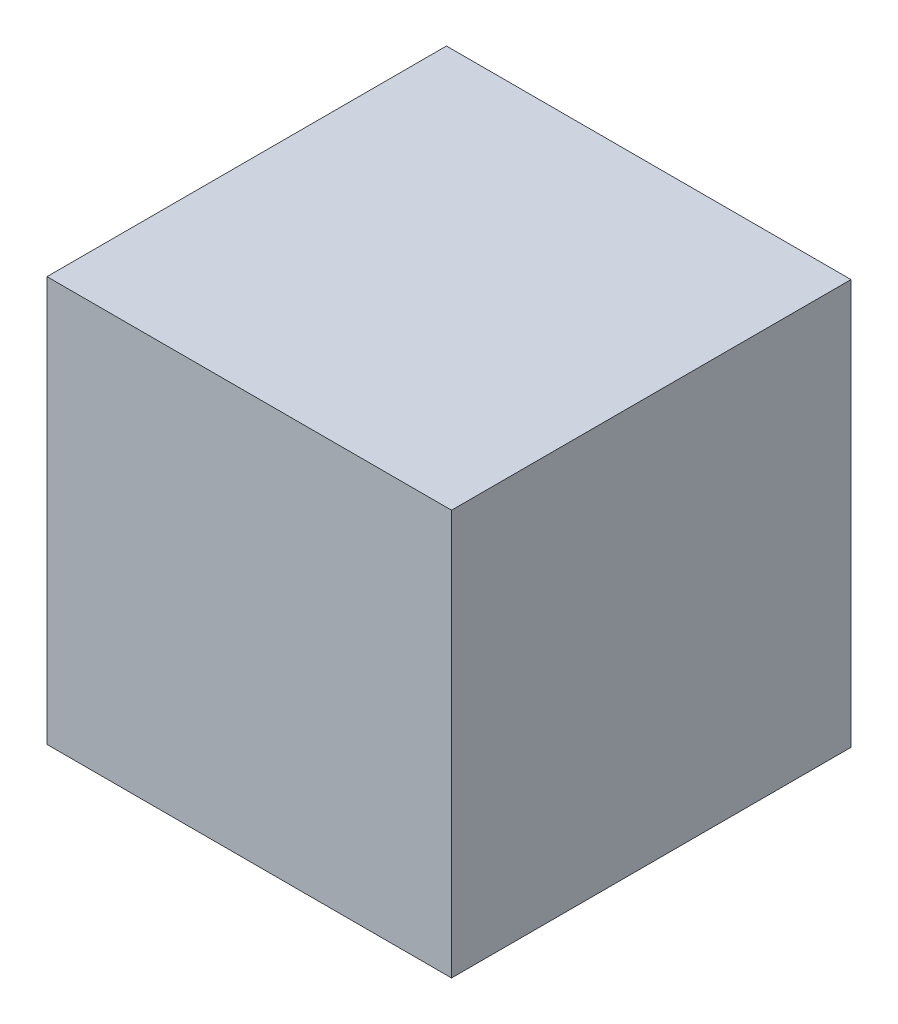
SolidWorks part; units mm, degrees
ref_plane "Front Plane" through (0, 0, 0) normal (0, 0, 1) x (1, 0, 0)
ref_plane "Top Plane" through (0, 0, 0) normal (0, 1, 0) x (1, 0, 0)
ref_plane "Right Plane" through (0, 0, 0) normal (1, 0, 0) x (0, 0, -1)
sketch "Sketch1" plane through (0, 0, 0) normal (0, 0, 1) x (1, 0, 0)
  line L1 (-84.8977, 48.4409) -> (12.8466, 48.4409)
  line L2 (-84.8977, 48.4409) -> (-84.8977, -49.4471)
  line L3 (-84.8977, -49.4471) -> (12.8466, -49.4471)
  line L4 (12.8466, 48.4409) -> (12.8466, -49.4471)
extrude "Boss-Extrude1" add sketch "Sketch1" along normal blind 96.52
